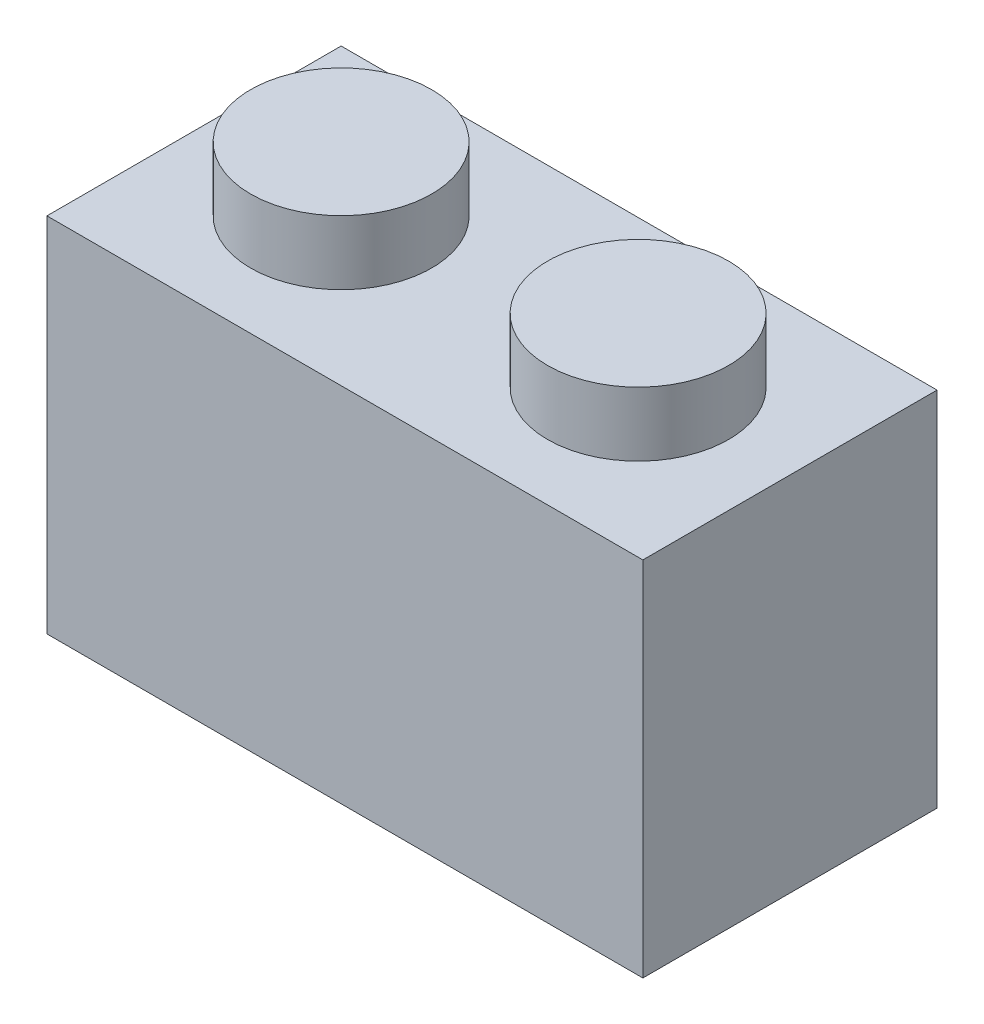
SolidWorks part; units mm, degrees
ref_plane "Спереди" through (0, 0, 0) normal (0, 0, 1) x (1, 0, 0)
ref_plane "Сверху" through (0, 0, 0) normal (0, 1, 0) x (1, 0, 0)
ref_plane "Справа" through (0, 0, 0) normal (1, 0, 0) x (0, 0, -1)
sketch "Эскиз1" plane through (0, 0, 0) normal (0, 1, 0) x (1, 0, 0)
  line L1 (7.9, -3.9) -> (-7.9, -3.9)
  line L2 (7.9, -3.9) -> (7.9, 3.9)
  line L3 (7.9, 3.9) -> (-7.9, 3.9)
  line L4 (-7.9, -3.9) -> (-7.9, 3.9)
  line L5 (7.9, -3.9) -> (-7.9, 3.9) construction
  line L6 (7.9, 3.9) -> (-7.9, -3.9) construction
  point P0 (0, 0)
  dimension "D1" = 15.8
  dimension "D2" = 7.8
extrude "Бобышка-Вытянуть1" add sketch "Эскиз1" along normal blind 9.6
sketch "Эскиз2" plane through (0, 9.6, 0) normal (0, 1, 0) x (1, 0, 0)
  line L0 (-7.9, 3.9) -> (-7.9, -3.9) construction
  line L1 (-7.9, -3.9) -> (7.9, -3.9) construction
  circle A0 centre (-4, 0) radius 2.4
  circle A1 centre (3.874, 0) radius 2.4
  dimension "D1" = 3.9
  dimension "D2" = 3.9
  dimension "D3" = 2
extrude "Бобышка-Вытянуть2" add sketch "Эскиз2" along normal blind 1.7
sketch "Эскиз3" plane through (0, 0, 0) normal (0, -1, 0) x (1, 0, 0)
  line L0 (-7.9, -3.9) -> (-7.9, 3.9) construction
  line L1 (7.9, -3.9) -> (-7.9, -3.9) construction
  circle A0 centre (-4, 0) radius 2.5
  circle A1 centre (3.874, 0) radius 2.5
  dimension "D1" = 3.9
  dimension "D2" = 3.9
  dimension "D3" = 2
extrude "Вырез-Вытянуть1" cut sketch "Эскиз3" against normal blind 1.8
